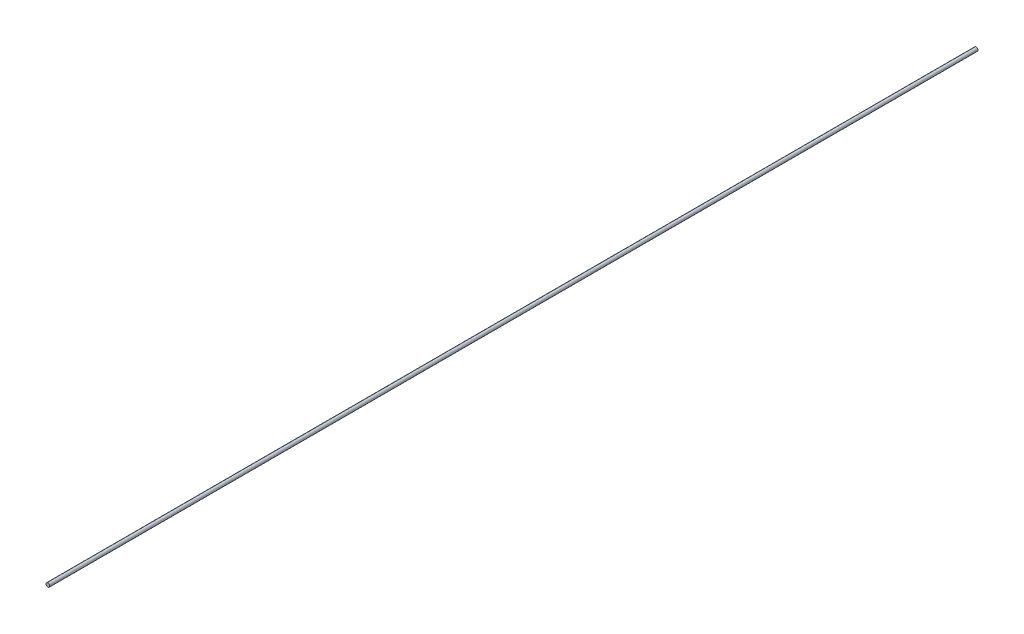
SolidWorks part; units mm, degrees
material "Настроенная пользователем пластмасса"
ref_plane "Спереди" through (0, 0, 0) normal (0, 0, 1) x (1, 0, 0)
ref_plane "Сверху" through (0, 0, 0) normal (0, 1, 0) x (1, 0, 0)
ref_plane "Справа" through (0, 0, 0) normal (1, 0, 0) x (0, 0, -1)
sketch "Эскиз1" plane through (0, 0, 0) normal (0, 0, 1) x (1, 0, 0)
  circle A0 centre (0, 0) radius 1
extrude "Бобышка-Вытянуть1" add sketch "Эскиз1" along normal blind 500
